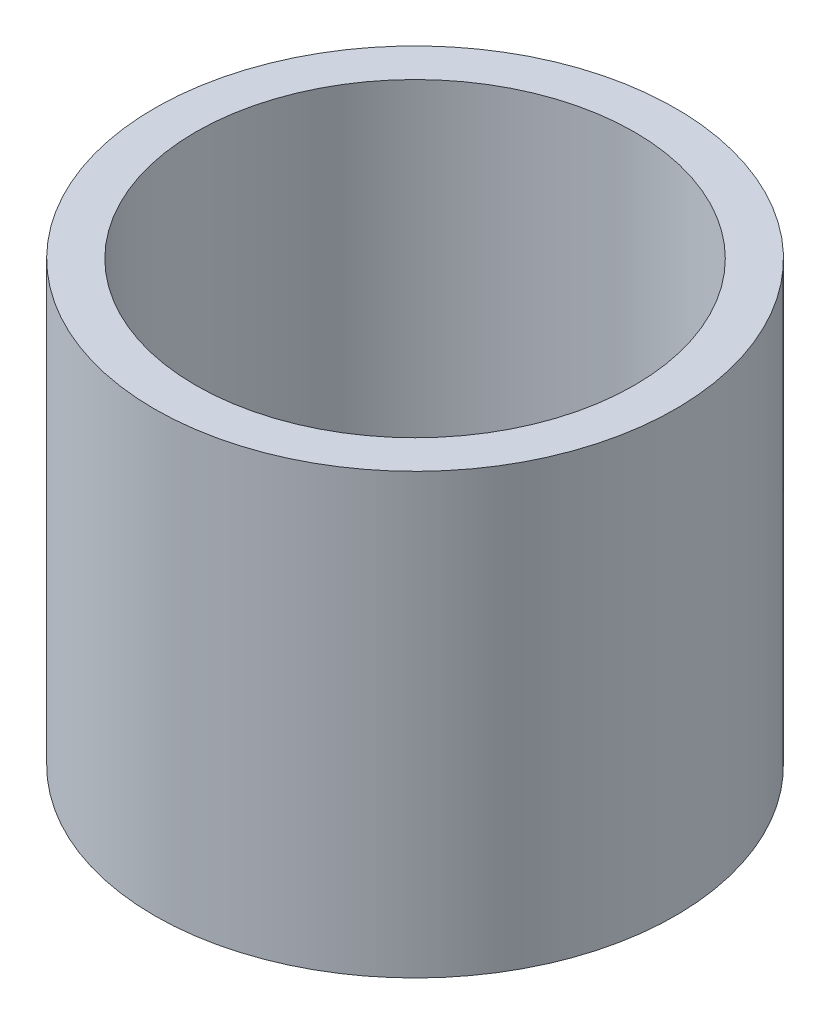
SolidWorks part; units mm, degrees
material "Brass"
ref_plane "Front Plane" through (0, 0, 0) normal (0, 0, 1) x (1, 0, 0)
ref_plane "Top Plane" through (0, 0, 0) normal (0, 1, 0) x (1, 0, 0)
ref_plane "Right Plane" through (0, 0, 0) normal (1, 0, 0) x (0, 0, -1)
sketch "Sketch1" plane through (0, 0, 0) normal (0, 1, 0) x (1, 0, 0)
  circle A0 centre (0, 0) radius 7.5406
  circle A1 centre (0, 0) radius 6.35
  dimension "D1" = 15.0812
  dimension "D2" = 12.7
extrude "Boss-Extrude1" add sketch "Sketch1" along normal blind 12.7
